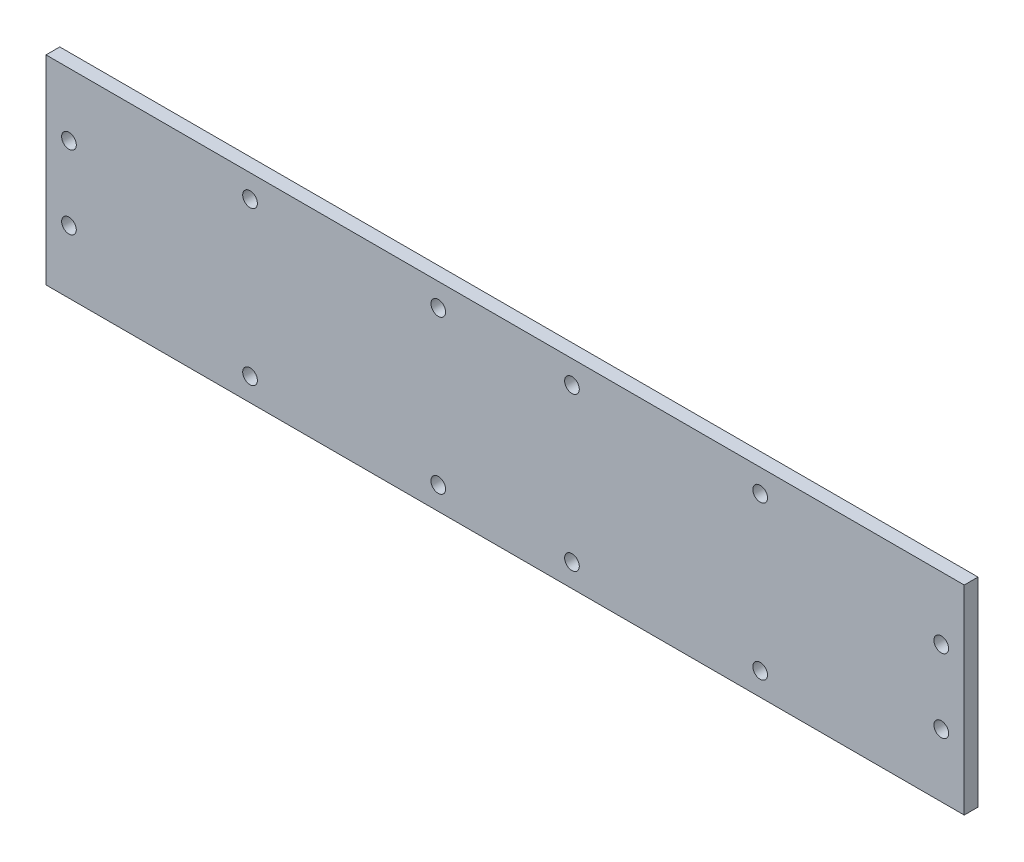
SolidWorks part; units mm, degrees
material "5052-O"
ref_plane "正面" through (0, 0, 0) normal (0, 0, 1) x (1, 0, 0)
ref_plane "平面" through (0, 0, 0) normal (0, 1, 0) x (1, 0, 0)
ref_plane "右側面" through (0, 0, 0) normal (1, 0, 0) x (0, 0, -1)
sketch "ｽｹｯﾁ1" plane through (0, 0, 0) normal (0, 0, 1) x (1, 0, 0)
  line L0 (0, 21.7) -> (0, -21.7) construction
  line L1 (100, -21.7) -> (-100, -21.7)
  line L2 (100, -21.7) -> (100, 21.7)
  line L3 (100, 21.7) -> (-100, 21.7)
  line L4 (-100, -21.7) -> (-100, 21.7)
  line L5 (100, -21.7) -> (-100, 21.7) construction
  line L6 (100, 21.7) -> (-100, -21.7) construction
  line L7 (-100, 0) -> (100, 0) construction
  line L8 (-55.5573, 16.7) -> (-14.5573, 16.7) construction
  line L9 (55.5573, 16.7) -> (14.5573, 16.7) construction
  line L10 (55.5573, -16.7) -> (14.5573, -16.7) construction
  line L11 (-55.5573, -16.7) -> (-14.5573, -16.7) construction
  line L12 (-95, 8) -> (-95, -8) construction
  line L13 (95, 8) -> (95, -8) construction
  circle A0 centre (-14.5573, 16.7) radius 1.6
  circle A1 centre (-55.5573, 16.7) radius 1.6
  circle A2 centre (14.5573, 16.7) radius 1.6
  circle A3 centre (55.5573, 16.7) radius 1.6
  circle A4 centre (55.5573, -16.7) radius 1.6
  circle A5 centre (14.5573, -16.7) radius 1.6
  circle A6 centre (-55.5573, -16.7) radius 1.6
  circle A7 centre (-14.5573, -16.7) radius 1.6
  circle A8 centre (-95, 8) radius 1.6
  circle A9 centre (-95, -8) radius 1.6
  circle A10 centre (95, -8) radius 1.6
  circle A11 centre (95, 8) radius 1.6
  point P0 (0, 0)
  point P30 (-95, 0)
  dimension "D3" = 3.2
  dimension "D5" = 29.1146
  dimension "D1" = 43.4
  dimension "D2" = 200
  dimension "D4" = 41
  dimension "D6" = 5
  dimension "D7" = 8
  dimension "D8" = 5
extrude "ﾎﾞｽ - 押し出し1" add sketch "ｽｹｯﾁ1" along normal blind 3
